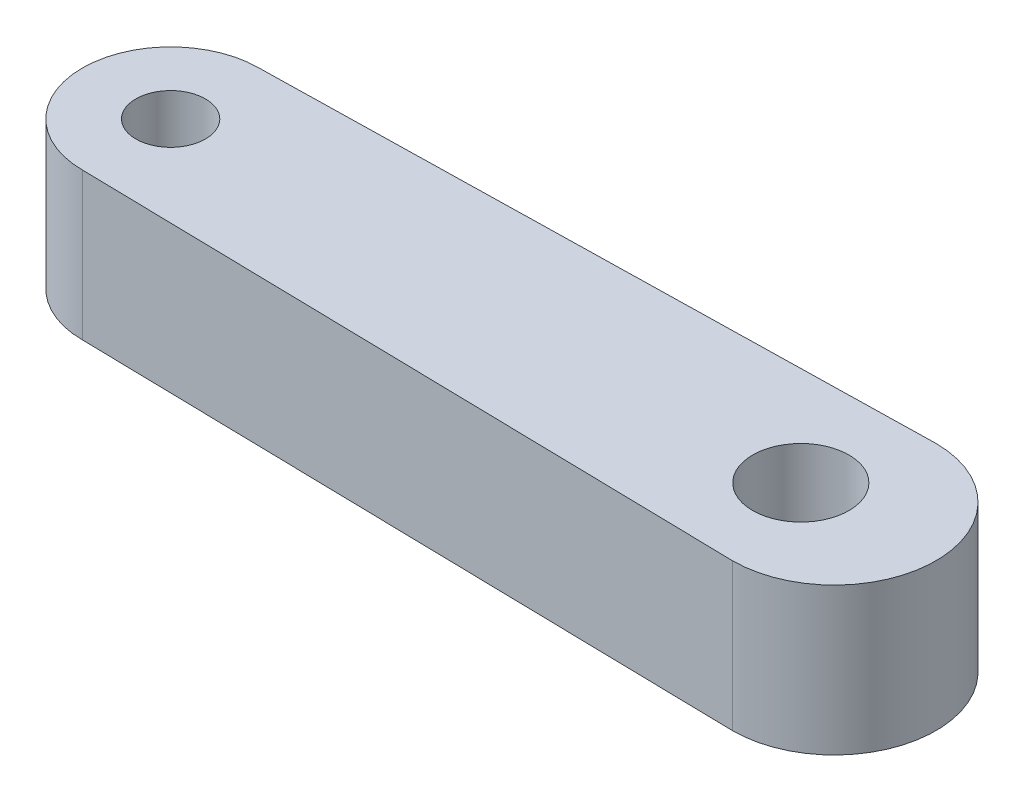
SolidWorks part; units mm, degrees
ref_plane "Front Plane" through (0, 0, 0) normal (0, 0, 1) x (1, 0, 0)
ref_plane "Top Plane" through (0, 0, 0) normal (0, 1, 0) x (1, 0, 0)
ref_plane "Right Plane" through (0, 0, 0) normal (1, 0, 0) x (0, 0, -1)
sketch "Sketch1" plane through (0, 0, 0) normal (0, 1, 0) x (1, 0, 0)
  line L0 (117.75, 0) -> (124, 0)
  line L1 (124, 19) -> (0, 16.5)
  line L2 (124, -19) -> (0, -16.5)
  circle A0 centre (0, 0) radius 6.5
  circle A1 centre (117.75, 0) radius 9
  arc A2 (123.2342, -18.9846) -> (123.2342, 18.9846) centre (124, 0) ccw
  arc A3 (0, 16.5) -> (0, -16.5) centre (0, 0) ccw
extrude "Boss-Extrude1" add sketch "Sketch1" along normal blind 27.5 contours L1 A3 L2 A2 A0 A1
sketch "Sketch2" plane through (0, 0, 0) normal (0, -1, 0) x (1, 0, 0)
  line L0 (117.75, 0) -> (94.4131, 0)
